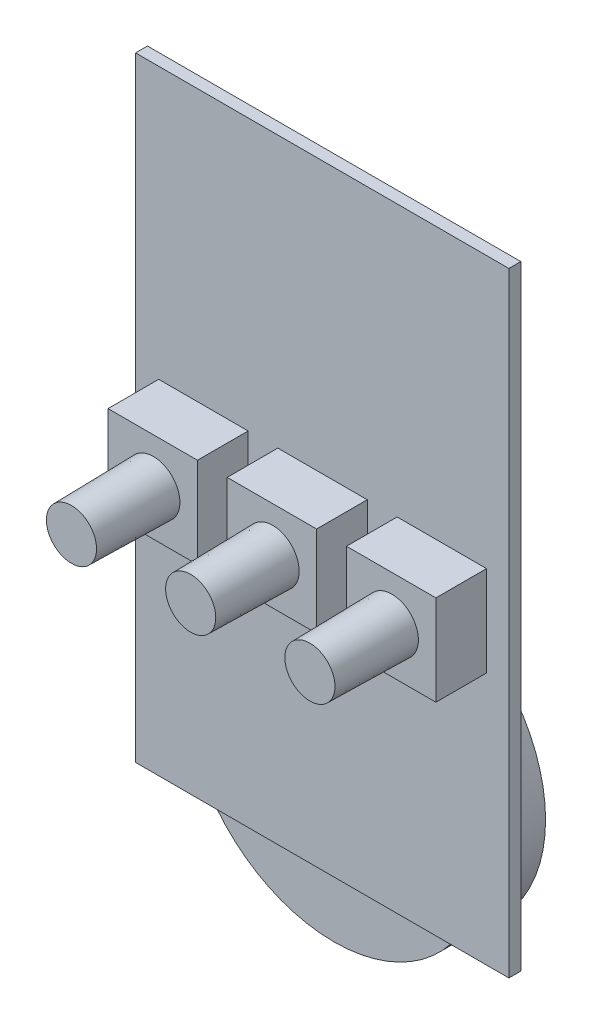
SolidWorks part; units mm, degrees
ref_plane "Front Plane" through (0, 0, 0) normal (0, 0, 1) x (1, 0, 0)
ref_plane "Top Plane" through (0, 0, 0) normal (0, 1, 0) x (1, 0, 0)
ref_plane "Right Plane" through (0, 0, 0) normal (1, 0, 0) x (0, 0, -1)
sketch "20" plane through (0, 0, 0) normal (0, 0, 1) x (1, 0, 0)
  line L0 (0, 0) -> (25.05, 0)
  line L1 (25.05, 0) -> (25.05, 41.23)
  line L2 (25.05, 41.23) -> (0, 41.23)
  line L3 (0, 41.23) -> (0, 0)
sketch "21" plane through (0, 0, 0) normal (0, 0, 1) x (1, 0, 0)
  line L0 (6.16, 25.0695) -> (6.16, 25.1305)
  line L1 (16.19, 25.2405) -> (16.19, 25.1795)
  line L2 (17, 3) -> (18.4, 3)
  line L3 (18.4, 3) -> (18.4, 5)
  line L4 (18.4, 5) -> (17, 5)
  line L5 (15, 3) -> (13.6, 3)
  line L6 (13.6, 3) -> (13.6, 5)
  line L7 (13.6, 5) -> (15, 5)
  line L8 (15.7, 3.3) -> (15.7, 4)
  line L9 (15.7, 4) -> (15.7, 4.7)
  line L10 (15.7, 4) -> (16.3, 3.4)
  line L11 (16.3, 3.4) -> (16.3, 4.6)
  line L12 (16.3, 4.6) -> (15.7, 4)
  line L13 (10, 3) -> (11.4, 3)
  line L14 (11.4, 3) -> (11.4, 5)
  line L15 (11.4, 5) -> (10, 5)
  line L16 (8, 3) -> (6.6, 3)
  line L17 (6.6, 3) -> (6.6, 5)
  line L18 (6.6, 5) -> (8, 5)
  line L19 (8.7, 3.3) -> (8.7, 4)
  line L20 (8.7, 4) -> (8.7, 4.7)
  line L21 (8.7, 4) -> (9.3, 3.4)
  line L22 (9.3, 3.4) -> (9.3, 4.6)
  line L23 (9.3, 4.6) -> (8.7, 4)
  line L24 (15.8, 9.3) -> (16.4, 9.3)
  line L25 (16.4, 9.3) -> (16.4, 10.1)
  line L26 (14.2, 9.3) -> (13.6, 9.3)
  line L27 (13.6, 9.3) -> (13.6, 10.1)
  line L28 (10.8, 9.3) -> (11.4, 9.3)
  line L29 (11.4, 9.3) -> (11.4, 10.1)
  line L30 (9.2, 9.3) -> (8.6, 9.3)
  line L31 (8.6, 9.3) -> (8.6, 10.1)
  line L32 (17.552, 22.159) -> (17.552, 17.841)
  line L33 (23.648, 17.841) -> (23.648, 22.159)
  line L34 (19.602, 23.048) -> (21.616, 23.048)
  line L35 (19.572, 16.952) -> (21.616, 16.952)
  line L36 (9.552, 22.159) -> (9.552, 17.841)
  line L37 (15.648, 17.841) -> (15.648, 22.159)
  line L38 (11.602, 23.048) -> (13.616, 23.048)
  line L39 (11.572, 16.952) -> (13.616, 16.952)
  line L40 (1.552, 22.159) -> (1.552, 17.841)
  line L41 (7.648, 17.841) -> (7.648, 22.159)
  line L42 (3.602, 23.048) -> (5.616, 23.048)
  line L43 (3.572, 16.952) -> (5.616, 16.952)
  arc A0 (6.2997, 25.1305) -> (6.0203, 25.1305) centre (6.16, 25.1305) ccw
  arc A1 (6.0203, 25.0695) -> (6.2997, 25.0695) centre (6.16, 25.0695) ccw
  arc A2 (16.0503, 25.1795) -> (16.3297, 25.1795) centre (16.19, 25.1795) ccw
  arc A3 (16.3297, 25.2405) -> (16.0503, 25.2405) centre (16.19, 25.2405) ccw
  arc A4 (18.4, 2.9492) -> (18.4, 3.0508) centre (18.4, 3) ccw
  arc A5 (17, 3.0508) -> (17, 2.9492) centre (17, 3) ccw
  arc A6 (18.4508, 5) -> (18.3492, 5) centre (18.4, 5) ccw
  arc A7 (18.3492, 3) -> (18.4508, 3) centre (18.4, 3) ccw
  arc A8 (17, 5.0508) -> (17, 4.9492) centre (17, 5) ccw
  arc A9 (18.4, 4.9492) -> (18.4, 5.0508) centre (18.4, 5) ccw
  arc A10 (13.6, 3.0508) -> (13.6, 2.9492) centre (13.6, 3) ccw
  arc A11 (15, 2.9492) -> (15, 3.0508) centre (15, 3) ccw
  arc A12 (13.6508, 5) -> (13.5492, 5) centre (13.6, 5) ccw
  arc A13 (13.5492, 3) -> (13.6508, 3) centre (13.6, 3) ccw
  arc A14 (15, 4.9492) -> (15, 5.0508) centre (15, 5) ccw
  arc A15 (13.6, 5.0508) -> (13.6, 4.9492) centre (13.6, 5) ccw
  arc A16 (15.7508, 4) -> (15.6492, 4) centre (15.7, 4) ccw
  arc A17 (15.6492, 3.3) -> (15.7508, 3.3) centre (15.7, 3.3) ccw
  arc A18 (15.7508, 4.7) -> (15.6492, 4.7) centre (15.7, 4.7) ccw
  arc A19 (15.6492, 4) -> (15.7508, 4) centre (15.7, 4) ccw
  arc A20 (16.2641, 3.3641) -> (16.3359, 3.4359) centre (16.3, 3.4) ccw
  arc A21 (15.7359, 4.0359) -> (15.6641, 3.9641) centre (15.7, 4) ccw
  arc A22 (16.3508, 4.6) -> (16.2492, 4.6) centre (16.3, 4.6) ccw
  arc A23 (16.2492, 3.4) -> (16.3508, 3.4) centre (16.3, 3.4) ccw
  arc A24 (15.6641, 4.0359) -> (15.7359, 3.9641) centre (15.7, 4) ccw
  arc A25 (16.3359, 4.5641) -> (16.2641, 4.6359) centre (16.3, 4.6) ccw
  arc A26 (11.4, 2.9492) -> (11.4, 3.0508) centre (11.4, 3) ccw
  arc A27 (10, 3.0508) -> (10, 2.9492) centre (10, 3) ccw
  arc A28 (11.4508, 5) -> (11.3492, 5) centre (11.4, 5) ccw
  arc A29 (11.3492, 3) -> (11.4508, 3) centre (11.4, 3) ccw
  arc A30 (10, 5.0508) -> (10, 4.9492) centre (10, 5) ccw
  arc A31 (11.4, 4.9492) -> (11.4, 5.0508) centre (11.4, 5) ccw
  arc A32 (6.6, 3.0508) -> (6.6, 2.9492) centre (6.6, 3) ccw
  arc A33 (8, 2.9492) -> (8, 3.0508) centre (8, 3) ccw
  arc A34 (6.6508, 5) -> (6.5492, 5) centre (6.6, 5) ccw
  arc A35 (6.5492, 3) -> (6.6508, 3) centre (6.6, 3) ccw
  arc A36 (8, 4.9492) -> (8, 5.0508) centre (8, 5) ccw
  arc A37 (6.6, 5.0508) -> (6.6, 4.9492) centre (6.6, 5) ccw
  arc A38 (8.7508, 4) -> (8.6492, 4) centre (8.7, 4) ccw
  arc A39 (8.6492, 3.3) -> (8.7508, 3.3) centre (8.7, 3.3) ccw
  arc A40 (8.7508, 4.7) -> (8.6492, 4.7) centre (8.7, 4.7) ccw
  arc A41 (8.6492, 4) -> (8.7508, 4) centre (8.7, 4) ccw
  arc A42 (9.2641, 3.3641) -> (9.3359, 3.4359) centre (9.3, 3.4) ccw
  arc A43 (8.7359, 4.0359) -> (8.6641, 3.9641) centre (8.7, 4) ccw
  arc A44 (9.3508, 4.6) -> (9.2492, 4.6) centre (9.3, 4.6) ccw
  arc A45 (9.2492, 3.4) -> (9.3508, 3.4) centre (9.3, 3.4) ccw
  arc A46 (8.6641, 4.0359) -> (8.7359, 3.9641) centre (8.7, 4) ccw
  arc A47 (9.3359, 4.5641) -> (9.2641, 4.6359) centre (9.3, 4.6) ccw
  arc A48 (16.4, 9.2492) -> (16.4, 9.3508) centre (16.4, 9.3) ccw
  arc A49 (15.8, 9.3508) -> (15.8, 9.2492) centre (15.8, 9.3) ccw
  arc A50 (16.4508, 10.1) -> (16.3492, 10.1) centre (16.4, 10.1) ccw
  arc A51 (16.3492, 9.3) -> (16.4508, 9.3) centre (16.4, 9.3) ccw
  arc A52 (13.6, 9.3508) -> (13.6, 9.2492) centre (13.6, 9.3) ccw
  arc A53 (14.2, 9.2492) -> (14.2, 9.3508) centre (14.2, 9.3) ccw
  arc A54 (13.6508, 10.1) -> (13.5492, 10.1) centre (13.6, 10.1) ccw
  arc A55 (13.5492, 9.3) -> (13.6508, 9.3) centre (13.6, 9.3) ccw
  arc A56 (11.4, 9.2492) -> (11.4, 9.3508) centre (11.4, 9.3) ccw
  arc A57 (10.8, 9.3508) -> (10.8, 9.2492) centre (10.8, 9.3) ccw
  arc A58 (11.4508, 10.1) -> (11.3492, 10.1) centre (11.4, 10.1) ccw
  arc A59 (11.3492, 9.3) -> (11.4508, 9.3) centre (11.4, 9.3) ccw
  arc A60 (8.6, 9.3508) -> (8.6, 9.2492) centre (8.6, 9.3) ccw
  arc A61 (9.2, 9.2492) -> (9.2, 9.3508) centre (9.2, 9.3) ccw
  arc A62 (8.6508, 10.1) -> (8.5492, 10.1) centre (8.6, 10.1) ccw
  arc A63 (8.5492, 9.3) -> (8.6508, 9.3) centre (8.6, 9.3) ccw
  arc A64 (17.5012, 17.841) -> (17.6028, 17.841) centre (17.552, 17.841) ccw
  arc A65 (17.6028, 22.159) -> (17.5012, 22.159) centre (17.552, 22.159) ccw
  arc A66 (23.6988, 22.159) -> (23.5972, 22.159) centre (23.648, 22.159) ccw
  arc A67 (23.5972, 17.841) -> (23.6988, 17.841) centre (23.648, 17.841) ccw
  arc A68 (21.616, 22.9972) -> (21.616, 23.0988) centre (21.616, 23.048) ccw
  arc A69 (19.602, 23.0988) -> (19.602, 22.9972) centre (19.602, 23.048) ccw
  arc A70 (21.616, 16.9012) -> (21.616, 17.0028) centre (21.616, 16.952) ccw
  arc A71 (19.572, 17.0028) -> (19.572, 16.9012) centre (19.572, 16.952) ccw
  circle A72 centre (20.6, 20) radius 1.778
  arc A73 (9.5012, 17.841) -> (9.6028, 17.841) centre (9.552, 17.841) ccw
  arc A74 (9.6028, 22.159) -> (9.5012, 22.159) centre (9.552, 22.159) ccw
  arc A75 (15.6988, 22.159) -> (15.5972, 22.159) centre (15.648, 22.159) ccw
  arc A76 (15.5972, 17.841) -> (15.6988, 17.841) centre (15.648, 17.841) ccw
  arc A77 (13.616, 22.9972) -> (13.616, 23.0988) centre (13.616, 23.048) ccw
  arc A78 (11.602, 23.0988) -> (11.602, 22.9972) centre (11.602, 23.048) ccw
  arc A79 (13.616, 16.9012) -> (13.616, 17.0028) centre (13.616, 16.952) ccw
  arc A80 (11.572, 17.0028) -> (11.572, 16.9012) centre (11.572, 16.952) ccw
  circle A81 centre (12.6, 20) radius 1.778
  arc A82 (1.5012, 17.841) -> (1.6028, 17.841) centre (1.552, 17.841) ccw
  arc A83 (1.6028, 22.159) -> (1.5012, 22.159) centre (1.552, 22.159) ccw
  arc A84 (7.6988, 22.159) -> (7.5972, 22.159) centre (7.648, 22.159) ccw
  arc A85 (7.5972, 17.841) -> (7.6988, 17.841) centre (7.648, 17.841) ccw
  arc A86 (5.616, 22.9972) -> (5.616, 23.0988) centre (5.616, 23.048) ccw
  arc A87 (3.602, 23.0988) -> (3.602, 22.9972) centre (3.602, 23.048) ccw
  arc A88 (5.616, 16.9012) -> (5.616, 17.0028) centre (5.616, 16.952) ccw
  arc A89 (3.572, 17.0028) -> (3.572, 16.9012) centre (3.572, 16.952) ccw
  circle A90 centre (4.6, 20) radius 1.778
sketch "22" plane through (0, 0, 0) normal (0, 0, 1) x (1, 0, 0)
  line L0 (20.01, 12.78) -> (5.01, 12.78)
  line L1 (20.01, 12.78) -> (23.06, 10.08)
  line L2 (5.01, 12.78) -> (1.96, 10.08)
  line L3 (1.96, 0.88) -> (6.96, -2.52)
  line L4 (18.06, -2.52) -> (23.06, 0.88)
  line L5 (1.96, 10.08) -> (1.96, 8.63)
  line L6 (23.06, 8.63) -> (23.06, 10.08)
  line L7 (23.06, 0.88) -> (23.06, 2.23)
  line L8 (1.96, 0.88) -> (1.96, 2.23)
  line L9 (18.515, 28.465) -> (17.245, 28.465)
  line L10 (22.9, 35.74) -> (2.7, 35.74)
  line L11 (2.7, 26.74) -> (10.6, 26.74)
  line L12 (10.6, 26.74) -> (15, 26.74)
  line L13 (15, 26.74) -> (22.9, 26.74)
  line L14 (22.9, 26.74) -> (22.9, 35.64)
  line L15 (2.7, 35.74) -> (2.7, 26.74)
  line L16 (15, 26.74) -> (15, 28.24)
  line L17 (15, 28.24) -> (10.6, 28.24)
  line L18 (10.6, 28.24) -> (10.6, 26.74)
  arc A0 (5.01, 12.8308) -> (5.01, 12.7292) centre (5.01, 12.78) ccw
  arc A1 (20.01, 12.7292) -> (20.01, 12.8308) centre (20.01, 12.78) ccw
  arc A2 (23.0263, 10.042) -> (23.0937, 10.118) centre (23.06, 10.08) ccw
  arc A3 (20.0437, 12.818) -> (19.9763, 12.742) centre (20.01, 12.78) ccw
  arc A4 (1.9263, 10.118) -> (1.9937, 10.042) centre (1.96, 10.08) ccw
  arc A5 (5.0437, 12.742) -> (4.9763, 12.818) centre (5.01, 12.78) ccw
  arc A6 (6.9314, -2.562) -> (6.9886, -2.478) centre (6.96, -2.52) ccw
  arc A7 (1.9886, 0.922) -> (1.9314, 0.838) centre (1.96, 0.88) ccw
  arc A8 (18.06, -2.52) -> (6.96, -2.52) centre (12.51, -11.6805) ccw
  arc A9 (18.0337, -2.5634) -> (18.0863, -2.4766) centre (18.06, -2.52) ccw
  arc A10 (6.9337, -2.4766) -> (6.9863, -2.5634) centre (6.96, -2.52) ccw
  arc A11 (23.0886, 0.838) -> (23.0314, 0.922) centre (23.06, 0.88) ccw
  arc A12 (18.0314, -2.478) -> (18.0886, -2.562) centre (18.06, -2.52) ccw
  arc A13 (1.9092, 8.63) -> (2.0108, 8.63) centre (1.96, 8.63) ccw
  arc A14 (2.0108, 10.08) -> (1.9092, 10.08) centre (1.96, 10.08) ccw
  arc A15 (23.1108, 10.08) -> (23.0092, 10.08) centre (23.06, 10.08) ccw
  arc A16 (23.0092, 8.63) -> (23.1108, 8.63) centre (23.06, 8.63) ccw
  arc A17 (23.1108, 2.23) -> (23.0092, 2.23) centre (23.06, 2.23) ccw
  arc A18 (23.0092, 0.88) -> (23.1108, 0.88) centre (23.06, 0.88) ccw
  arc A19 (2.0108, 2.23) -> (1.9092, 2.23) centre (1.96, 2.23) ccw
  arc A20 (1.9092, 0.88) -> (2.0108, 0.88) centre (1.96, 0.88) ccw
  arc A21 (17.245, 28.5158) -> (17.245, 28.4142) centre (17.245, 28.465) ccw
  arc A22 (18.515, 28.4142) -> (18.515, 28.5158) centre (18.515, 28.465) ccw
  arc A23 (2.7, 35.7908) -> (2.7, 35.6892) centre (2.7, 35.74) ccw
  arc A24 (22.9, 35.6892) -> (22.9, 35.7908) centre (22.9, 35.74) ccw
  arc A25 (10.6, 26.6892) -> (10.6, 26.7908) centre (10.6, 26.74) ccw
  arc A26 (2.7, 26.7908) -> (2.7, 26.6892) centre (2.7, 26.74) ccw
  arc A27 (15, 26.6892) -> (15, 26.7908) centre (15, 26.74) ccw
  arc A28 (10.6, 26.7908) -> (10.6, 26.6892) centre (10.6, 26.74) ccw
  arc A29 (22.9, 26.6892) -> (22.9, 26.7908) centre (22.9, 26.74) ccw
  arc A30 (15, 26.7908) -> (15, 26.6892) centre (15, 26.74) ccw
  arc A31 (22.9508, 35.64) -> (22.8492, 35.64) centre (22.9, 35.64) ccw
  arc A32 (22.8492, 26.74) -> (22.9508, 26.74) centre (22.9, 26.74) ccw
  arc A33 (2.6492, 26.74) -> (2.7508, 26.74) centre (2.7, 26.74) ccw
  arc A34 (2.7508, 35.74) -> (2.6492, 35.74) centre (2.7, 35.74) ccw
  arc A35 (15.0508, 28.24) -> (14.9492, 28.24) centre (15, 28.24) ccw
  arc A36 (14.9492, 26.74) -> (15.0508, 26.74) centre (15, 26.74) ccw
  arc A37 (10.6, 28.2908) -> (10.6, 28.1892) centre (10.6, 28.24) ccw
  arc A38 (15, 28.1892) -> (15, 28.2908) centre (15, 28.24) ccw
  arc A39 (10.5492, 26.74) -> (10.6508, 26.74) centre (10.6, 26.74) ccw
  arc A40 (10.6508, 28.24) -> (10.5492, 28.24) centre (10.6, 28.24) ccw
sketch "23" plane through (0, 0, 0) normal (0, 0, 1) x (1, 0, 0)
  point P0 (19.34, 13.99)
  point P1 (6.16, 25.1)
  point P2 (16.19, 25.21)
  point P3 (16, 4)
  point P4 (9, 4)
  point P5 (15, 10)
  point P6 (10, 10)
  point P7 (15, 7)
  point P8 (9, 7)
  point P9 (20.6, 20)
  point P10 (12.6, 20)
  point P11 (4.6, 20)
  point P12 (4.62, 26.18)
sketch "24" plane through (0, 0, 0) normal (0, 0, 1) x (1, 0, 0)
  point P0 (12.51, 5.43)
  point P1 (12.8, 31.24)
sketch "51" plane through (0, 0, 0) normal (0, 0, 1) x (1, 0, 0)
  line L0 (20.305, 13.203) -> (18.375, 13.203)
  line L1 (20.305, 14.777) -> (18.375, 14.777)
  line L2 (6.516, 24.668) -> (5.804, 24.668)
  line L3 (6.516, 25.519) -> (5.804, 25.519)
  line L4 (15.834, 25.642) -> (16.546, 25.642)
  line L5 (15.834, 24.791) -> (16.546, 24.791)
  line L6 (13.5776, 9.3396) -> (13.5776, 10.6604)
  line L7 (13.5776, 10.6604) -> (16.4224, 10.6604)
  line L8 (16.4224, 10.6604) -> (16.4224, 9.3396)
  line L9 (16.4224, 9.3396) -> (13.5776, 9.3396)
  line L10 (8.5776, 9.3396) -> (8.5776, 10.6604)
  line L11 (8.5776, 10.6604) -> (11.4224, 10.6604)
  line L12 (11.4224, 10.6604) -> (11.4224, 9.3396)
  line L13 (11.4224, 9.3396) -> (8.5776, 9.3396)
  line L14 (14.644, 7.432) -> (15.356, 7.432)
  line L15 (14.644, 6.581) -> (15.356, 6.581)
  line L16 (8.644, 7.432) -> (9.356, 7.432)
  line L17 (8.644, 6.581) -> (9.356, 6.581)
  line L18 (19.584, 23.048) -> (18.06, 23.048)
  line L19 (18.06, 23.048) -> (17.552, 22.54)
  line L20 (23.648, 22.54) -> (23.14, 23.048)
  line L21 (23.14, 23.048) -> (21.616, 23.048)
  line L22 (17.552, 17.46) -> (18.06, 16.952)
  line L23 (18.06, 16.952) -> (19.584, 16.952)
  line L24 (23.648, 17.46) -> (23.14, 16.952)
  line L25 (23.14, 16.952) -> (21.616, 16.952)
  line L26 (23.648, 22.54) -> (23.648, 22.159)
  line L27 (23.648, 17.46) -> (23.648, 17.841)
  line L28 (17.552, 17.46) -> (17.552, 17.841)
  line L29 (17.552, 22.54) -> (17.552, 22.159)
  line L30 (19.33, 17.46) -> (20.092, 17.46)
  line L31 (21.108, 17.46) -> (21.87, 17.46)
  line L32 (20.092, 17.46) -> (20.981, 17.841)
  line L33 (11.584, 23.048) -> (10.06, 23.048)
  line L34 (10.06, 23.048) -> (9.552, 22.54)
  line L35 (15.648, 22.54) -> (15.14, 23.048)
  line L36 (15.14, 23.048) -> (13.616, 23.048)
  line L37 (9.552, 17.46) -> (10.06, 16.952)
  line L38 (10.06, 16.952) -> (11.584, 16.952)
  line L39 (15.648, 17.46) -> (15.14, 16.952)
  line L40 (15.14, 16.952) -> (13.616, 16.952)
  line L41 (15.648, 22.54) -> (15.648, 22.159)
  line L42 (15.648, 17.46) -> (15.648, 17.841)
  line L43 (9.552, 17.46) -> (9.552, 17.841)
  line L44 (9.552, 22.54) -> (9.552, 22.159)
  line L45 (11.33, 17.46) -> (12.092, 17.46)
  line L46 (13.108, 17.46) -> (13.87, 17.46)
  line L47 (12.092, 17.46) -> (12.981, 17.841)
  line L48 (3.584, 23.048) -> (2.06, 23.048)
  line L49 (2.06, 23.048) -> (1.552, 22.54)
  line L50 (7.648, 22.54) -> (7.14, 23.048)
  line L51 (7.14, 23.048) -> (5.616, 23.048)
  line L52 (1.552, 17.46) -> (2.06, 16.952)
  line L53 (2.06, 16.952) -> (3.584, 16.952)
  line L54 (7.648, 17.46) -> (7.14, 16.952)
  line L55 (7.14, 16.952) -> (5.616, 16.952)
  line L56 (7.648, 22.54) -> (7.648, 22.159)
  line L57 (7.648, 17.46) -> (7.648, 17.841)
  line L58 (1.552, 17.46) -> (1.552, 17.841)
  line L59 (1.552, 22.54) -> (1.552, 22.159)
  line L60 (3.33, 17.46) -> (4.092, 17.46)
  line L61 (5.108, 17.46) -> (5.87, 17.46)
  line L62 (4.092, 17.46) -> (4.981, 17.841)
  arc A0 (18.375, 13.2284) -> (18.375, 13.1776) centre (18.375, 13.203) ccw
  arc A1 (20.305, 13.1776) -> (20.305, 13.2284) centre (20.305, 13.203) ccw
  arc A2 (18.375, 14.8024) -> (18.375, 14.7516) centre (18.375, 14.777) ccw
  arc A3 (20.305, 14.7516) -> (20.305, 14.8024) centre (20.305, 14.777) ccw
  arc A4 (5.804, 24.6934) -> (5.804, 24.6426) centre (5.804, 24.668) ccw
  arc A5 (6.516, 24.6426) -> (6.516, 24.6934) centre (6.516, 24.668) ccw
  arc A6 (5.804, 25.5444) -> (5.804, 25.4936) centre (5.804, 25.519) ccw
  arc A7 (6.516, 25.4936) -> (6.516, 25.5444) centre (6.516, 25.519) ccw
  arc A8 (16.546, 25.6166) -> (16.546, 25.6674) centre (16.546, 25.642) ccw
  arc A9 (15.834, 25.6674) -> (15.834, 25.6166) centre (15.834, 25.642) ccw
  arc A10 (16.546, 24.7656) -> (16.546, 24.8164) centre (16.546, 24.791) ccw
  arc A11 (15.834, 24.8164) -> (15.834, 24.7656) centre (15.834, 24.791) ccw
  arc A12 (13.6157, 10.6604) -> (13.5395, 10.6604) centre (13.5776, 10.6604) ccw
  arc A13 (13.5395, 9.3396) -> (13.6157, 9.3396) centre (13.5776, 9.3396) ccw
  arc A14 (16.4224, 10.6223) -> (16.4224, 10.6985) centre (16.4224, 10.6604) ccw
  arc A15 (13.5776, 10.6985) -> (13.5776, 10.6223) centre (13.5776, 10.6604) ccw
  arc A16 (16.3843, 9.3396) -> (16.4605, 9.3396) centre (16.4224, 9.3396) ccw
  arc A17 (16.4605, 10.6604) -> (16.3843, 10.6604) centre (16.4224, 10.6604) ccw
  arc A18 (13.5776, 9.3777) -> (13.5776, 9.3015) centre (13.5776, 9.3396) ccw
  arc A19 (16.4224, 9.3015) -> (16.4224, 9.3777) centre (16.4224, 9.3396) ccw
  arc A20 (8.6157, 10.6604) -> (8.5395, 10.6604) centre (8.5776, 10.6604) ccw
  arc A21 (8.5395, 9.3396) -> (8.6157, 9.3396) centre (8.5776, 9.3396) ccw
  arc A22 (11.4224, 10.6223) -> (11.4224, 10.6985) centre (11.4224, 10.6604) ccw
  arc A23 (8.5776, 10.6985) -> (8.5776, 10.6223) centre (8.5776, 10.6604) ccw
  arc A24 (11.3843, 9.3396) -> (11.4605, 9.3396) centre (11.4224, 9.3396) ccw
  arc A25 (11.4605, 10.6604) -> (11.3843, 10.6604) centre (11.4224, 10.6604) ccw
  arc A26 (8.5776, 9.3777) -> (8.5776, 9.3015) centre (8.5776, 9.3396) ccw
  arc A27 (11.4224, 9.3015) -> (11.4224, 9.3777) centre (11.4224, 9.3396) ccw
  arc A28 (15.356, 7.4066) -> (15.356, 7.4574) centre (15.356, 7.432) ccw
  arc A29 (14.644, 7.4574) -> (14.644, 7.4066) centre (14.644, 7.432) ccw
  arc A30 (15.356, 6.5556) -> (15.356, 6.6064) centre (15.356, 6.581) ccw
  arc A31 (14.644, 6.6064) -> (14.644, 6.5556) centre (14.644, 6.581) ccw
  arc A32 (9.356, 7.4066) -> (9.356, 7.4574) centre (9.356, 7.432) ccw
  arc A33 (8.644, 7.4574) -> (8.644, 7.4066) centre (8.644, 7.432) ccw
  arc A34 (9.356, 6.5556) -> (9.356, 6.6064) centre (9.356, 6.581) ccw
  arc A35 (8.644, 6.6064) -> (8.644, 6.5556) centre (8.644, 6.581) ccw
  arc A36 (18.06, 23.0988) -> (18.06, 22.9972) centre (18.06, 23.048) ccw
  arc A37 (19.584, 22.9972) -> (19.584, 23.0988) centre (19.584, 23.048) ccw
  arc A38 (17.5161, 22.5759) -> (17.5879, 22.5041) centre (17.552, 22.54) ccw
  arc A39 (18.0959, 23.0121) -> (18.0241, 23.0839) centre (18.06, 23.048) ccw
  arc A40 (23.1759, 23.0839) -> (23.1041, 23.0121) centre (23.14, 23.048) ccw
  arc A41 (23.6121, 22.5041) -> (23.6839, 22.5759) centre (23.648, 22.54) ccw
  arc A42 (21.616, 23.0988) -> (21.616, 22.9972) centre (21.616, 23.048) ccw
  arc A43 (23.14, 22.9972) -> (23.14, 23.0988) centre (23.14, 23.048) ccw
  arc A44 (18.0241, 16.9161) -> (18.0959, 16.9879) centre (18.06, 16.952) ccw
  arc A45 (17.5879, 17.4959) -> (17.5161, 17.4241) centre (17.552, 17.46) ccw
  arc A46 (19.584, 16.9012) -> (19.584, 17.0028) centre (19.584, 16.952) ccw
  arc A47 (18.06, 17.0028) -> (18.06, 16.9012) centre (18.06, 16.952) ccw
  arc A48 (23.1041, 16.9879) -> (23.1759, 16.9161) centre (23.14, 16.952) ccw
  arc A49 (23.6839, 17.4241) -> (23.6121, 17.4959) centre (23.648, 17.46) ccw
  arc A50 (21.616, 17.0028) -> (21.616, 16.9012) centre (21.616, 16.952) ccw
  arc A51 (23.14, 16.9012) -> (23.14, 17.0028) centre (23.14, 16.952) ccw
  arc A52 (23.5972, 22.159) -> (23.6988, 22.159) centre (23.648, 22.159) ccw
  arc A53 (23.6988, 22.54) -> (23.5972, 22.54) centre (23.648, 22.54) ccw
  arc A54 (23.6988, 17.841) -> (23.5972, 17.841) centre (23.648, 17.841) ccw
  arc A55 (23.5972, 17.46) -> (23.6988, 17.46) centre (23.648, 17.46) ccw
  arc A56 (17.6028, 17.841) -> (17.5012, 17.841) centre (17.552, 17.841) ccw
  arc A57 (17.5012, 17.46) -> (17.6028, 17.46) centre (17.552, 17.46) ccw
  arc A58 (17.5012, 22.159) -> (17.6028, 22.159) centre (17.552, 22.159) ccw
  arc A59 (17.6028, 22.54) -> (17.5012, 22.54) centre (17.552, 22.54) ccw
  arc A60 (20.092, 17.4092) -> (20.092, 17.5108) centre (20.092, 17.46) ccw
  arc A61 (19.33, 17.5108) -> (19.33, 17.4092) centre (19.33, 17.46) ccw
  arc A62 (21.87, 17.4092) -> (21.87, 17.5108) centre (21.87, 17.46) ccw
  arc A63 (21.108, 17.5108) -> (21.108, 17.4092) centre (21.108, 17.46) ccw
  arc A64 (21.001, 17.7943) -> (20.961, 17.8877) centre (20.981, 17.841) ccw
  arc A65 (20.072, 17.5067) -> (20.112, 17.4133) centre (20.092, 17.46) ccw
  arc A66 (10.06, 23.0988) -> (10.06, 22.9972) centre (10.06, 23.048) ccw
  arc A67 (11.584, 22.9972) -> (11.584, 23.0988) centre (11.584, 23.048) ccw
  arc A68 (9.5161, 22.5759) -> (9.5879, 22.5041) centre (9.552, 22.54) ccw
  arc A69 (10.0959, 23.0121) -> (10.0241, 23.0839) centre (10.06, 23.048) ccw
  arc A70 (15.1759, 23.0839) -> (15.1041, 23.0121) centre (15.14, 23.048) ccw
  arc A71 (15.6121, 22.5041) -> (15.6839, 22.5759) centre (15.648, 22.54) ccw
  arc A72 (13.616, 23.0988) -> (13.616, 22.9972) centre (13.616, 23.048) ccw
  arc A73 (15.14, 22.9972) -> (15.14, 23.0988) centre (15.14, 23.048) ccw
  arc A74 (10.0241, 16.9161) -> (10.0959, 16.9879) centre (10.06, 16.952) ccw
  arc A75 (9.5879, 17.4959) -> (9.5161, 17.4241) centre (9.552, 17.46) ccw
  arc A76 (11.584, 16.9012) -> (11.584, 17.0028) centre (11.584, 16.952) ccw
  arc A77 (10.06, 17.0028) -> (10.06, 16.9012) centre (10.06, 16.952) ccw
  arc A78 (15.1041, 16.9879) -> (15.1759, 16.9161) centre (15.14, 16.952) ccw
  arc A79 (15.6839, 17.4241) -> (15.6121, 17.4959) centre (15.648, 17.46) ccw
  arc A80 (13.616, 17.0028) -> (13.616, 16.9012) centre (13.616, 16.952) ccw
  arc A81 (15.14, 16.9012) -> (15.14, 17.0028) centre (15.14, 16.952) ccw
  arc A82 (15.5972, 22.159) -> (15.6988, 22.159) centre (15.648, 22.159) ccw
  arc A83 (15.6988, 22.54) -> (15.5972, 22.54) centre (15.648, 22.54) ccw
  arc A84 (15.6988, 17.841) -> (15.5972, 17.841) centre (15.648, 17.841) ccw
  arc A85 (15.5972, 17.46) -> (15.6988, 17.46) centre (15.648, 17.46) ccw
  arc A86 (9.6028, 17.841) -> (9.5012, 17.841) centre (9.552, 17.841) ccw
  arc A87 (9.5012, 17.46) -> (9.6028, 17.46) centre (9.552, 17.46) ccw
  arc A88 (9.5012, 22.159) -> (9.6028, 22.159) centre (9.552, 22.159) ccw
  arc A89 (9.6028, 22.54) -> (9.5012, 22.54) centre (9.552, 22.54) ccw
  arc A90 (12.092, 17.4092) -> (12.092, 17.5108) centre (12.092, 17.46) ccw
  arc A91 (11.33, 17.5108) -> (11.33, 17.4092) centre (11.33, 17.46) ccw
  arc A92 (13.87, 17.4092) -> (13.87, 17.5108) centre (13.87, 17.46) ccw
  arc A93 (13.108, 17.5108) -> (13.108, 17.4092) centre (13.108, 17.46) ccw
  arc A94 (13.001, 17.7943) -> (12.961, 17.8877) centre (12.981, 17.841) ccw
  arc A95 (12.072, 17.5067) -> (12.112, 17.4133) centre (12.092, 17.46) ccw
  arc A96 (2.06, 23.0988) -> (2.06, 22.9972) centre (2.06, 23.048) ccw
  arc A97 (3.584, 22.9972) -> (3.584, 23.0988) centre (3.584, 23.048) ccw
  arc A98 (1.5161, 22.5759) -> (1.5879, 22.5041) centre (1.552, 22.54) ccw
  arc A99 (2.0959, 23.0121) -> (2.0241, 23.0839) centre (2.06, 23.048) ccw
  arc A100 (7.1759, 23.0839) -> (7.1041, 23.0121) centre (7.14, 23.048) ccw
  arc A101 (7.6121, 22.5041) -> (7.6839, 22.5759) centre (7.648, 22.54) ccw
  arc A102 (5.616, 23.0988) -> (5.616, 22.9972) centre (5.616, 23.048) ccw
  arc A103 (7.14, 22.9972) -> (7.14, 23.0988) centre (7.14, 23.048) ccw
  arc A104 (2.0241, 16.9161) -> (2.0959, 16.9879) centre (2.06, 16.952) ccw
  arc A105 (1.5879, 17.4959) -> (1.5161, 17.4241) centre (1.552, 17.46) ccw
  arc A106 (3.584, 16.9012) -> (3.584, 17.0028) centre (3.584, 16.952) ccw
  arc A107 (2.06, 17.0028) -> (2.06, 16.9012) centre (2.06, 16.952) ccw
  arc A108 (7.1041, 16.9879) -> (7.1759, 16.9161) centre (7.14, 16.952) ccw
  arc A109 (7.6839, 17.4241) -> (7.6121, 17.4959) centre (7.648, 17.46) ccw
  arc A110 (5.616, 17.0028) -> (5.616, 16.9012) centre (5.616, 16.952) ccw
  arc A111 (7.14, 16.9012) -> (7.14, 17.0028) centre (7.14, 16.952) ccw
  arc A112 (7.5972, 22.159) -> (7.6988, 22.159) centre (7.648, 22.159) ccw
  arc A113 (7.6988, 22.54) -> (7.5972, 22.54) centre (7.648, 22.54) ccw
  arc A114 (7.6988, 17.841) -> (7.5972, 17.841) centre (7.648, 17.841) ccw
  arc A115 (7.5972, 17.46) -> (7.6988, 17.46) centre (7.648, 17.46) ccw
  arc A116 (1.6028, 17.841) -> (1.5012, 17.841) centre (1.552, 17.841) ccw
  arc A117 (1.5012, 17.46) -> (1.6028, 17.46) centre (1.552, 17.46) ccw
  arc A118 (1.5012, 22.159) -> (1.6028, 22.159) centre (1.552, 22.159) ccw
  arc A119 (1.6028, 22.54) -> (1.5012, 22.54) centre (1.552, 22.54) ccw
  arc A120 (4.092, 17.4092) -> (4.092, 17.5108) centre (4.092, 17.46) ccw
  arc A121 (3.33, 17.5108) -> (3.33, 17.4092) centre (3.33, 17.46) ccw
  arc A122 (5.87, 17.4092) -> (5.87, 17.5108) centre (5.87, 17.46) ccw
  arc A123 (5.108, 17.5108) -> (5.108, 17.4092) centre (5.108, 17.46) ccw
  arc A124 (5.001, 17.7943) -> (4.961, 17.8877) centre (4.981, 17.841) ccw
  arc A125 (4.072, 17.5067) -> (4.112, 17.4133) centre (4.092, 17.46) ccw
sketch "52" plane through (0, 0, 0) normal (0, 0, 1) x (1, 0, 0)
  line L0 (1.96, 7.98) -> (1.96, 5.98)
  line L1 (1.96, 4.88) -> (1.96, 2.88)
  line L2 (23.06, 7.98) -> (23.06, 5.98)
  line L3 (23.06, 4.88) -> (23.06, 2.88)
  line L4 (1.96, 7.98) -> (1.06, 7.98)
  line L5 (1.06, 7.98) -> (1.06, 5.98)
  line L6 (1.06, 5.98) -> (1.96, 5.98)
  line L7 (1.96, 4.88) -> (1.06, 4.88)
  line L8 (1.06, 4.88) -> (1.06, 2.88)
  line L9 (1.06, 2.88) -> (1.96, 2.88)
  line L10 (23.06, 2.88) -> (23.96, 2.88)
  line L11 (23.96, 2.88) -> (23.96, 4.88)
  line L12 (23.96, 4.88) -> (23.06, 4.88)
  line L13 (23.06, 5.98) -> (23.96, 5.98)
  line L14 (23.96, 5.98) -> (23.96, 7.98)
  line L15 (23.96, 7.98) -> (23.06, 7.98)
  line L16 (21.8, 27.84) -> (21.8, 34.64)
  line L17 (21.8, 34.64) -> (3.8, 34.64)
  line L18 (3.8, 27.84) -> (3.8, 34.64)
  line L19 (21.8, 27.84) -> (15, 27.84)
  line L20 (3.8, 27.84) -> (10.6, 27.84)
  arc A0 (1.9092, 5.98) -> (2.0108, 5.98) centre (1.96, 5.98) ccw
  arc A1 (2.0108, 7.98) -> (1.9092, 7.98) centre (1.96, 7.98) ccw
  arc A2 (1.9092, 2.88) -> (2.0108, 2.88) centre (1.96, 2.88) ccw
  arc A3 (2.0108, 4.88) -> (1.9092, 4.88) centre (1.96, 4.88) ccw
  arc A4 (23.0092, 5.98) -> (23.1108, 5.98) centre (23.06, 5.98) ccw
  arc A5 (23.1108, 7.98) -> (23.0092, 7.98) centre (23.06, 7.98) ccw
  arc A6 (23.0092, 2.88) -> (23.1108, 2.88) centre (23.06, 2.88) ccw
  arc A7 (23.1108, 4.88) -> (23.0092, 4.88) centre (23.06, 4.88) ccw
  arc A8 (1.06, 8.0308) -> (1.06, 7.9292) centre (1.06, 7.98) ccw
  arc A9 (1.96, 7.9292) -> (1.96, 8.0308) centre (1.96, 7.98) ccw
  arc A10 (1.0092, 5.98) -> (1.1108, 5.98) centre (1.06, 5.98) ccw
  arc A11 (1.1108, 7.98) -> (1.0092, 7.98) centre (1.06, 7.98) ccw
  arc A12 (1.96, 5.9292) -> (1.96, 6.0308) centre (1.96, 5.98) ccw
  arc A13 (1.06, 6.0308) -> (1.06, 5.9292) centre (1.06, 5.98) ccw
  arc A14 (1.06, 4.9308) -> (1.06, 4.8292) centre (1.06, 4.88) ccw
  arc A15 (1.96, 4.8292) -> (1.96, 4.9308) centre (1.96, 4.88) ccw
  arc A16 (1.0092, 2.88) -> (1.1108, 2.88) centre (1.06, 2.88) ccw
  arc A17 (1.1108, 4.88) -> (1.0092, 4.88) centre (1.06, 4.88) ccw
  arc A18 (1.96, 2.8292) -> (1.96, 2.9308) centre (1.96, 2.88) ccw
  arc A19 (1.06, 2.9308) -> (1.06, 2.8292) centre (1.06, 2.88) ccw
  arc A20 (23.96, 2.8292) -> (23.96, 2.9308) centre (23.96, 2.88) ccw
  arc A21 (23.06, 2.9308) -> (23.06, 2.8292) centre (23.06, 2.88) ccw
  arc A22 (24.0108, 4.88) -> (23.9092, 4.88) centre (23.96, 4.88) ccw
  arc A23 (23.9092, 2.88) -> (24.0108, 2.88) centre (23.96, 2.88) ccw
  arc A24 (23.06, 4.9308) -> (23.06, 4.8292) centre (23.06, 4.88) ccw
  arc A25 (23.96, 4.8292) -> (23.96, 4.9308) centre (23.96, 4.88) ccw
  arc A26 (23.96, 5.9292) -> (23.96, 6.0308) centre (23.96, 5.98) ccw
  arc A27 (23.06, 6.0308) -> (23.06, 5.9292) centre (23.06, 5.98) ccw
  arc A28 (24.0108, 7.98) -> (23.9092, 7.98) centre (23.96, 7.98) ccw
  arc A29 (23.9092, 5.98) -> (24.0108, 5.98) centre (23.96, 5.98) ccw
  arc A30 (23.06, 8.0308) -> (23.06, 7.9292) centre (23.06, 7.98) ccw
  arc A31 (23.96, 7.9292) -> (23.96, 8.0308) centre (23.96, 7.98) ccw
  circle A32 centre (12.51, 5.43) radius 10
  arc A33 (21.8508, 34.64) -> (21.7492, 34.64) centre (21.8, 34.64) ccw
  arc A34 (21.7492, 27.84) -> (21.8508, 27.84) centre (21.8, 27.84) ccw
  arc A35 (3.8, 34.6908) -> (3.8, 34.5892) centre (3.8, 34.64) ccw
  arc A36 (21.8, 34.5892) -> (21.8, 34.6908) centre (21.8, 34.64) ccw
  arc A37 (3.8508, 34.64) -> (3.7492, 34.64) centre (3.8, 34.64) ccw
  arc A38 (3.7492, 27.84) -> (3.8508, 27.84) centre (3.8, 27.84) ccw
  arc A39 (15, 27.8908) -> (15, 27.7892) centre (15, 27.84) ccw
  arc A40 (21.8, 27.7892) -> (21.8, 27.8908) centre (21.8, 27.84) ccw
  arc A41 (10.6, 27.7892) -> (10.6, 27.8908) centre (10.6, 27.84) ccw
  arc A42 (3.8, 27.8908) -> (3.8, 27.7892) centre (3.8, 27.84) ccw
extrude "Boss-Extrude1" add sketch "20" against normal blind 0.8
sketch "Sketch13" plane through (0, 0, 0) normal (0, 0, 1) x (1, 0, 0)
  line L1 (1.5541, 23.039) -> (7.5541, 23.039)
  line L2 (1.5541, 23.039) -> (1.5541, 16.9752)
  line L3 (1.5541, 16.9752) -> (7.5541, 16.9752)
  line L4 (7.5541, 23.039) -> (7.5541, 16.9752)
  line L5 (9.5464, 23.039) -> (15.5464, 23.039)
  line L6 (9.5464, 23.039) -> (9.5464, 16.9752)
  line L7 (9.5464, 16.9752) -> (15.5464, 16.9752)
  line L8 (15.5464, 23.039) -> (15.5464, 16.9752)
  line L9 (17.5517, 23.039) -> (23.5517, 23.039)
  line L10 (17.5517, 23.039) -> (17.5517, 16.9752)
  line L11 (17.5517, 16.9752) -> (23.5517, 16.9752)
  line L12 (23.5517, 23.039) -> (23.5517, 16.9752)
  dimension "D1" = 6
  dimension "D2" = 6
  dimension "D3" = 6
extrude "Boss-Extrude2" add sketch "Sketch13" along normal blind 3.4
sketch "Sketch14" plane through (0, 0, 3.4) normal (0, 0, 1) x (1, 0, 0)
  circle A0 centre (4.6, 20) radius 1.778
  circle A1 centre (12.6, 20) radius 1.778
  circle A2 centre (20.6, 20) radius 1.778
extrude "Boss-Extrude3" add sketch "Sketch14" along normal blind 5.5 draft 1
sketch "Sketch15" plane through (0, 0, -0.8) normal (0, 0, 1) x (1, 0, 0)
  circle A0 centre (12.51, 5.43) radius 10
extrude "Boss-Extrude4" add sketch "Sketch15" against normal blind 4.2
